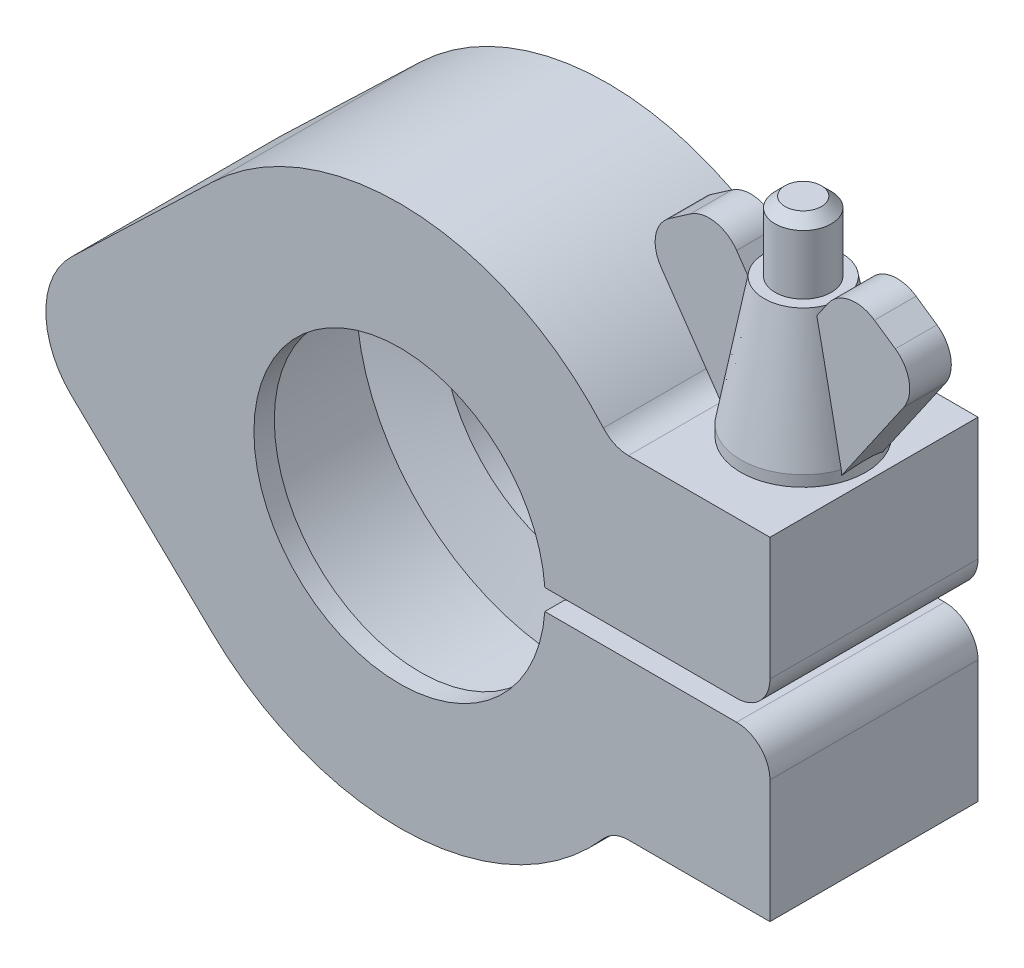
SolidWorks part; units mm, degrees
material "ASTM A36 Steel"
ref_plane "Front Plane" through (0, 0, 0) normal (0, 0, 1) x (1, 0, 0)
ref_plane "Top Plane" through (0, 0, 0) normal (0, 1, 0) x (1, 0, 0)
ref_plane "Right Plane" through (0, 0, 0) normal (1, 0, 0) x (0, 0, -1)
sketch "Sketch1" plane through (0, 0, 0) normal (0, 0, 1) x (1, 0, 0)
  line L0 (28.2575, -12.7) -> (28.2575, -3.3337)
  line L1 (28.2575, 12.7) -> (17.4625, 12.7)
  line L2 (28.2575, -12.7) -> (17.4625, -12.7)
  line L3 (-14.2875, 14.8921) -> (-25.0337, 4.5822)
  line L4 (-25.0337, -4.5822) -> (-14.2875, -14.8921)
  line L5 (25.7175, -0.7938) -> (6.5948, -0.7938)
  line L6 (6.5948, -0.7938) -> (6.5948, 0.7938)
  line L7 (6.5948, 0.7938) -> (25.7175, 0.7938)
  line L8 (28.2575, 3.3337) -> (28.2575, 12.7)
  arc A0 (-25.0337, 4.5822) -> (-25.0337, -4.5822) centre (-20.6375, 0) ccw
  arc A1 (-14.2875, -14.8921) -> (15.5488, -13.5699) centre (0, 0) ccw
  arc A2 (-14.2875, 14.8921) -> (15.5488, 13.5699) centre (0, 0) cw
  arc A3 (17.4625, -12.7) -> (15.5488, -13.5699) centre (17.4625, -15.24) ccw
  arc A4 (17.4625, 12.7) -> (15.5488, 13.5699) centre (17.4625, 15.24) cw
  arc A5 (25.7175, -0.7938) -> (28.2575, -3.3337) centre (25.7175, -3.3337) cw
  arc A6 (25.7175, 0.7938) -> (28.2575, 3.3337) centre (25.7175, 3.3337) ccw
  circle A7 centre (0, 0) radius 11.1125 construction
  circle A8 centre (0, 0) radius 16.256 construction
  point P11 (6.5948, 0)
  point P22 (0, 11.1125)
  point P23 (0, 16.256)
  dimension "D1" = 2.54
  dimension "D2" = 6.35
  dimension "D4" = 6.35
  dimension "D5" = 41.275
  dimension "D8" = 2.54
  dimension "D9" = 22.225
  dimension "D10" = 32.512
  dimension "D12" = 2.54
  dimension "D3" = 25.4
  dimension "D6" = 7.62
  dimension "D7" = 55.245
  dimension "D11" = 1.5875
extrude "Boss-Extrude1" add sketch "Sketch1" along normal mid plane 15.875
sketch "Sketch2" plane through (0, 0, 0) normal (1, 0, 0) x (0, 0, -1)
  line L0 (5.0038, 16.256) -> (-5.0038, 16.256)
  line L1 (17.0412, 0) -> (38.2928, 0) construction
  line L2 (-17.0412, 0) -> (-17.0412, 11.1125)
  line L3 (-17.0412, 11.1125) -> (-6.382, 11.1125)
  line L4 (-17.0412, 0) -> (17.0412, 0)
  line L5 (17.0412, 0) -> (17.0412, 11.1125)
  line L6 (17.0412, 11.1125) -> (6.382, 11.1125)
  line L7 (6.382, 11.1125) -> (5.0038, 16.256)
  line L8 (-6.382, 11.1125) -> (-5.0038, 16.256)
  dimension "D1" = 75
  dimension "D2" = 10.0076
revolve "Cut-Revolve1" cut sketch "Sketch2" angle 360 about L1
sketch "Sketch3" plane through (0, 0, 0) normal (0, 0, 1) x (1, 0, 0)
  line L0 (22.86, 12.7) -> (27.6225, 12.7)
  line L1 (27.6225, 12.7) -> (27.6225, 13.5304)
  line L2 (27.6225, 13.5304) -> (25.8345, 23.2833)
  line L3 (25.8345, 23.2833) -> (25.0041, 23.2833)
  line L4 (25.0041, 23.2833) -> (25.0041, 27.813)
  line L5 (25.0041, 27.813) -> (24.2421, 28.575)
  line L6 (24.2421, 28.575) -> (22.86, 28.575)
  line L7 (22.86, 28.575) -> (22.86, 23.2833)
  line L8 (22.86, 28.575) -> (22.86, 40.1357) construction
  line L9 (28.2575, 12.7) -> (17.4625, 12.7) construction
  line L10 (22.86, 23.2833) -> (22.86, 17.9917)
  line L11 (22.86, 17.9917) -> (22.86, 12.7)
  dimension "D1" = 9.525
  dimension "D2" = 4.2883
  dimension "D3" = 15.875
  dimension "D4" = 45
  dimension "D5" = 0.762
revolve "Revolve1" add sketch "Sketch3" angle 360 about L8
sketch "Sketch4" plane through (0, 0, 0) normal (0, 0, 1) x (1, 0, 0)
  line L0 (22.86, 10.2693) -> (22.86, 4.4547) construction
  line L1 (25.2614, 22.4529) -> (26.3518, 24.0328)
  line L2 (29.885, 24.6806) -> (31.4745, 23.5836)
  line L3 (32.1222, 20.0503) -> (27.0494, 12.7)
  line L4 (25.2614, 22.4529) -> (27.0494, 12.7)
  line L5 (22.86, 12.7) -> (27.6225, 12.7) construction
  line L6 (27.6225, 13.5304) -> (25.8345, 23.2833) construction
  line L7 (20.4586, 22.4529) -> (18.6706, 12.7)
  line L8 (13.5978, 20.0503) -> (18.6706, 12.7)
  line L9 (15.835, 24.6806) -> (14.2455, 23.5836)
  line L10 (20.4586, 22.4529) -> (19.3682, 24.0328)
  arc A0 (31.4745, 23.5836) -> (32.1222, 20.0503) centre (30.0318, 21.4931) cw
  arc A1 (26.3518, 24.0328) -> (29.885, 24.6806) centre (28.4423, 22.5901) cw
  arc A4 (19.3682, 24.0328) -> (15.835, 24.6806) centre (17.2777, 22.5901) ccw
  arc A5 (14.2455, 23.5836) -> (13.5978, 20.0503) centre (15.6882, 21.4931) ccw
  dimension "D2" = 2.54
  dimension "D1" = 45
extrude "Boss-Extrude2" add sketch "Sketch4" along normal mid plane 3.175
